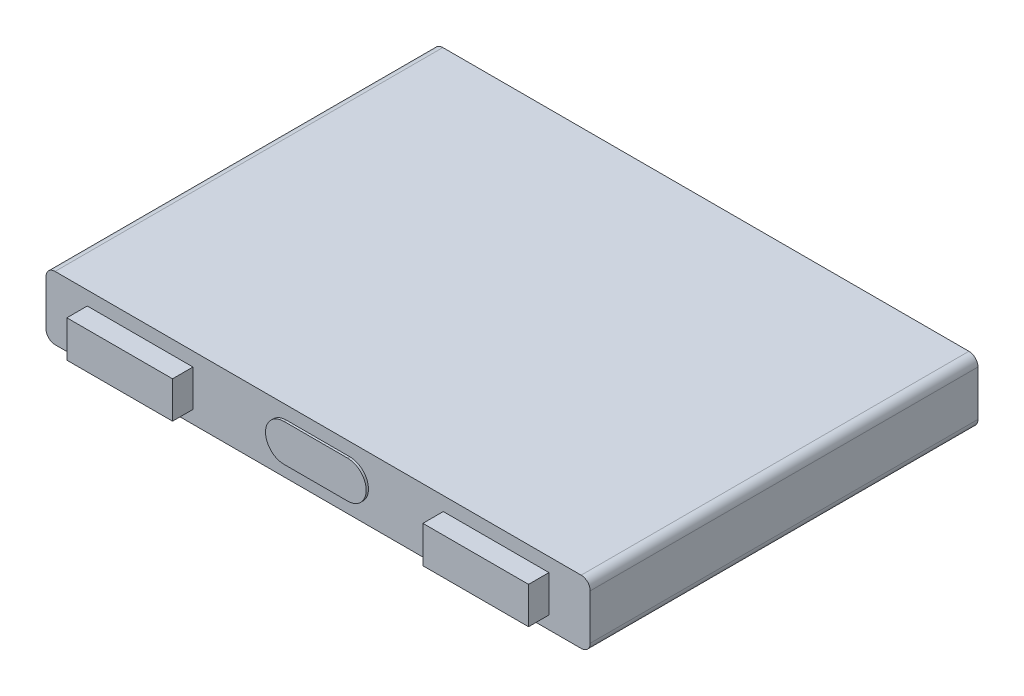
SolidWorks part; units mm, degrees
ref_plane "前视基准面" through (0, 0, 0) normal (0, 0, 1) x (1, 0, 0)
ref_plane "上视基准面" through (0, 0, 0) normal (0, 1, 0) x (1, 0, 0)
ref_plane "右视基准面" through (0, 0, 0) normal (1, 0, 0) x (0, 0, -1)
sketch "Sketch1" plane through (0, 0, 0) normal (0, 1, 0) x (1, 0, 0)
  line L1 (-60, 42.75) -> (60, 42.75)
  line L2 (-60, 42.75) -> (-60, -42.75)
  line L3 (-60, -42.75) -> (60, -42.75)
  line L4 (60, 42.75) -> (60, -42.75)
  line L5 (-60, 42.75) -> (60, -42.75) construction
  line L6 (-60, -42.75) -> (60, 42.75) construction
  point P0 (0, 0)
  dimension "D1" = 120
  dimension "D2" = 85.5
extrude "Boss-Extrude1" add sketch "Sketch1" along normal blind 14
sketch "Sketch2" plane through (0, 0, 42.75) normal (0, 0, 1) x (1, 0, 0)
  line L0 (-60, 14) -> (-60, 0) construction
  line L1 (-27.6, 2.8446) -> (-50.9, 2.8446)
  line L2 (-27.6, 2.8446) -> (-27.6, 10.9446)
  line L3 (-27.6, 10.9446) -> (-50.9, 10.9446)
  line L4 (-50.9, 2.8446) -> (-50.9, 10.9446)
  line L5 (-27.6, 2.8446) -> (-50.9, 10.9446) construction
  line L6 (-27.6, 10.9446) -> (-50.9, 2.8446) construction
  line L7 (0, 0) -> (0, 14) construction
  line L8 (-60, 14) -> (60, 14) construction
  line L9 (27.6, 10.9446) -> (50.9, 2.8446) construction
  line L10 (27.6, 2.8446) -> (50.9, 10.9446) construction
  line L11 (50.9, 2.8446) -> (50.9, 10.9446)
  line L12 (27.6, 10.9446) -> (50.9, 10.9446)
  line L13 (27.6, 2.8446) -> (27.6, 10.9446)
  line L14 (27.6, 2.8446) -> (50.9, 2.8446)
  point P0 (-39.25, 6.8946)
  point P16 (39.25, 6.8946)
  dimension "D1" = 9.1
  dimension "D2" = 23.3
  dimension "D3" = 8.1
extrude "Boss-Extrude2" add sketch "Sketch2" along normal blind 4.5
fillet "Fillet2" radius 2 4 edges at (-60, 14, 0) (-60, 0, 0) (60, 0, 0) (60, 14, 0)
sketch "Sketch4" plane through (0, 0, 42.75) normal (0, 0, 1) x (1, 0, 0)
  line L2 (-7, 11.1) -> (7, 11.1)
  line L4 (58, 14) -> (-58, 14)
  line L5 (-60, 12) -> (-60, 2)
  line L6 (-58, 0) -> (58, 0)
  line L7 (60, 2) -> (60, 12)
  line L8 (58, 14) -> (-58, 14)
  line L9 (-60, 12) -> (-60, 2)
  line L10 (-58, 0) -> (58, 0)
  line L11 (60, 2) -> (60, 12)
  line L12 (-7, 2.9) -> (7, 2.9)
  arc A0 (-7, 11.1) -> (-7, 2.9) centre (-7, 7) ccw
  arc A1 (7, 2.9) -> (7, 11.1) centre (7, 7) ccw
  arc A4 (-58, 14) -> (-60, 12) centre (-58, 12) ccw
  arc A5 (-60, 2) -> (-58, 0) centre (-58, 2) ccw
  arc A6 (58, 0) -> (60, 2) centre (58, 2) ccw
  arc A7 (60, 12) -> (58, 14) centre (58, 12) ccw
  arc A8 (-58, 14) -> (-60, 12) centre (-58, 12) ccw
  arc A9 (-60, 2) -> (-58, 0) centre (-58, 2) ccw
  arc A10 (58, 0) -> (60, 2) centre (58, 2) ccw
  arc A11 (60, 12) -> (58, 14) centre (58, 12) ccw
  point P2 (0, 7)
  dimension "D2" = 14
  dimension "D3" = 8.2
  dimension "D1" = 0
extrude "Boss-Extrude3" add sketch "Sketch4" along normal blind 0.5 contours L12 A1 L2 A0
